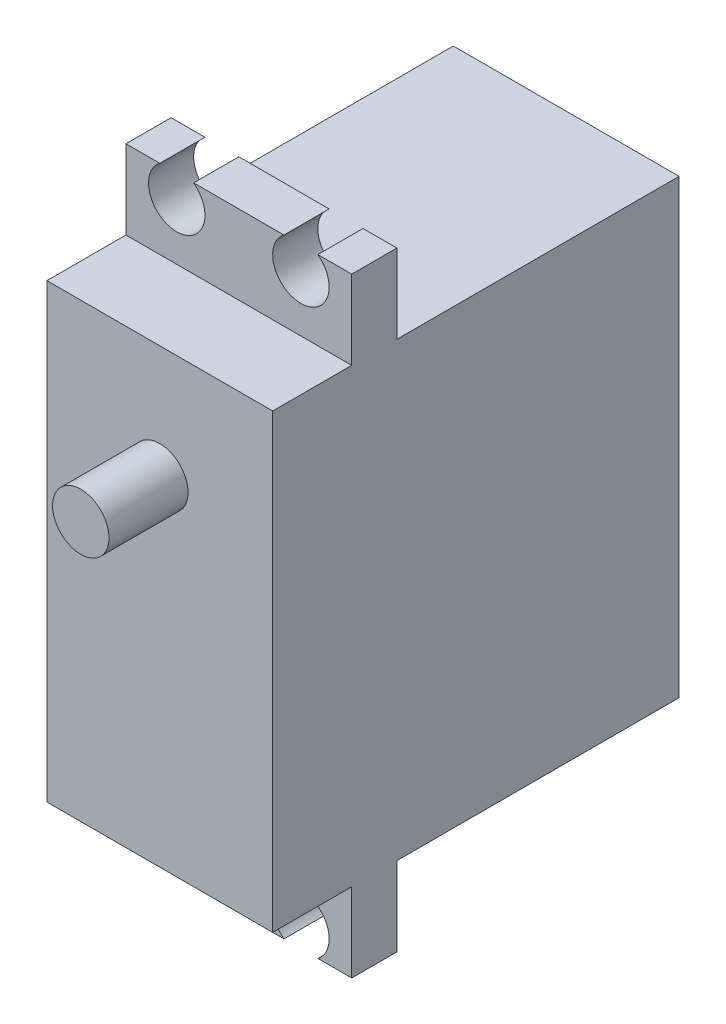
SolidWorks part; units mm, degrees
ref_plane "Plan de face" through (0, 0, 0) normal (0, 0, 1) x (1, 0, 0)
ref_plane "Plan de dessus" through (0, 0, 0) normal (0, 1, 0) x (1, 0, 0)
ref_plane "Plan de droite" through (0, 0, 0) normal (1, 0, 0) x (0, 0, -1)
sketch "Esquisse1" plane through (0, 0, 0) normal (0, 0, 1) x (1, 0, 0)
  line L1 (0, 0) -> (20, 0)
  line L2 (0, 0) -> (0, -40)
  line L3 (0, -40) -> (20, -40)
  line L4 (20, 0) -> (20, -40)
  dimension "D1" = 40
  dimension "D2" = 20
extrude "Boss.-Extru.1" add sketch "Esquisse1" along normal blind 36
sketch "Esquisse2" plane through (0, 0, 36) normal (0, 0, 1) x (1, 0, 0)
  line L1 (0, 0) -> (20, 0)
  line L2 (0, 0) -> (0, 7)
  line L3 (0, 7) -> (20, 7)
  line L4 (20, 0) -> (20, 7)
  line L5 (0, -40) -> (20, -40)
  line L6 (0, -40) -> (0, -47)
  line L7 (0, -47) -> (20, -47)
  line L8 (20, -40) -> (20, -47)
  dimension "D1" = 7
  dimension "D2" = 7
extrude "Boss.-Extru.2" add sketch "Esquisse2" against normal blind 11
sketch "Esquisse3" plane through (0, 0, 36) normal (0, 0, 1) x (1, 0, 0)
  line L0 (20, -47) -> (20, 7) construction
  line L1 (0, -47) -> (20, -47)
  line L2 (0, -47) -> (0, -40)
  line L3 (0, -40) -> (20, -40)
  line L4 (20, -47) -> (20, -40)
  line L6 (0, 7) -> (20, 7)
  line L7 (0, 7) -> (0, 0)
  line L8 (0, 0) -> (20, 0)
  line L9 (20, 7) -> (20, 0)
  dimension "D1" = 7
  dimension "D2" = 7
extrude "Enlèv. mat.-Extru.1" cut sketch "Esquisse3" against normal blind 7
sketch "Esquisse4" plane through (0, 0, 36) normal (0, 0, 1) x (1, 0, 0)
  line L0 (0, 0) -> (0, -40) construction
  line L1 (0, 0) -> (20, 0) construction
  circle A0 centre (10, -10) radius 2.5
  dimension "D1" = 5
  dimension "D2" = 10
  dimension "D3" = 10
extrude "Boss.-Extru.3" add sketch "Esquisse4" along normal blind 7
sketch "Esquisse5" plane through (0, 0, 29) normal (0, 0, 1) x (1, 0, 0)
  line L0 (0, -47) -> (20, -47) construction
  line L1 (20, -47) -> (20, -40) construction
  line L2 (0, -40) -> (0, -47) construction
  circle A0 centre (4.5, -45) radius 2.5
  circle A1 centre (15.5, -45) radius 2.5
  dimension "D3" = 5
  dimension "D4" = 5
  dimension "D1" = 2
  dimension "D2" = 2
  dimension "D5" = 4.5
  dimension "D6" = 4.5
extrude "Enlèv. mat.-Extru.2" cut sketch "Esquisse5" against normal blind 7
sketch "Esquisse6" plane through (0, 0, 29) normal (0, 0, 1) x (1, 0, 0)
  line L0 (20, 7) -> (0, 7) construction
  line L1 (20, 0) -> (20, 7) construction
  line L2 (0, 7) -> (0, 0) construction
  circle A0 centre (4.5, 5) radius 2.5
  circle A1 centre (15.5, 5) radius 2.5
  dimension "D1" = 5
  dimension "D2" = 5
  dimension "D3" = 2
  dimension "D4" = 2
  dimension "D5" = 4.5
  dimension "D6" = 4.5
extrude "Enlèv. mat.-Extru.3" cut sketch "Esquisse6" against normal blind 7
